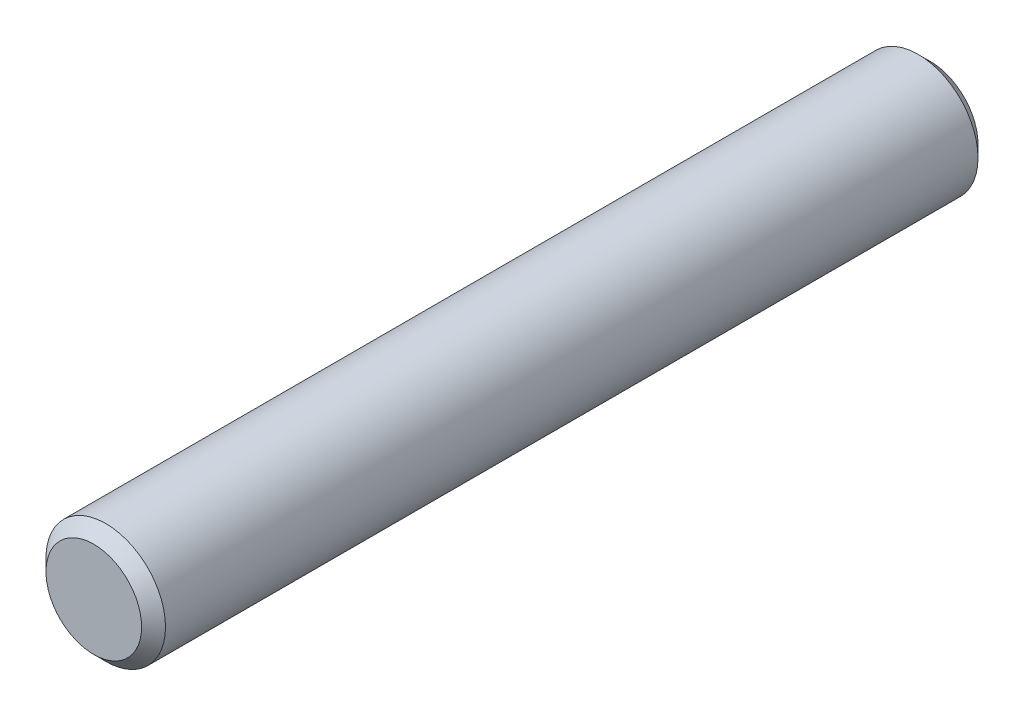
SolidWorks part; units mm, degrees
ref_plane "Front" through (0, 0, 0) normal (0, 0, 1) x (1, 0, 0)
ref_plane "Top" through (0, 0, 0) normal (0, 1, 0) x (1, 0, 0)
ref_plane "Right" through (0, 0, 0) normal (1, 0, 0) x (0, 0, -1)
sketch "Sketch1" plane through (0, 0, 0) normal (0, 0, 1) x (1, 0, 0)
  circle A0 centre (0, 0) radius 6.35
  dimension "Diameter" = 12.7
sketch "Sketch2" plane through (0, 0, 0) normal (1, 0, 0) x (0, 0, -1)
  line L0 (-152.4, 0) -> (152.4, 0) construction
  line L1 (-101.6, 6.35) -> (-101.6, -6.35) construction
  line L2 (17.4625, 0) -> (-17.4625, 0) construction
  line L3 (101.6, 6.35) -> (101.6, -6.35) construction
  line L4 (-152.4, 6.35) -> (-152.4, -6.35) construction
  line L5 (152.4, 6.35) -> (152.4, -6.35) construction
  point P3 (-101.6, 0)
  point P8 (0, 0)
  point P9 (101.6, 0)
  point P15 (-152.4, 0)
  point P18 (152.4, 0)
  dimension "D1" = 12.7
  dimension "Length" = 304.8
  dimension "D2" = 50.8
  dimension "D3" = 50.8
sketch "Sketch3" plane through (0, 0, 0) normal (0, 0, 1) x (1, 0, 0)
  circle A0 centre (0, 0) radius 6.35
  dimension "D1" = 12.7
extrude "Boss-Extrude1" add sketch "Sketch3" along normal mid plane 88.9
chamfer "Chamfer1" distance 1.27 angle 45 2 edges at (6.35, 0, -44.45) (6.35, 0, 44.45)
equation "\"D1@Sketch3\" = \"Diameter@Sketch1\""
equation "\"D1@Boss-Extrude1\" = \"Length@Sketch2\""
equation "\"D1@Chamfer1\" = \"Diameter@Sketch1\" * .1"
equation "\"D1@Sketch2\" = \"Diameter@Sketch1\""
